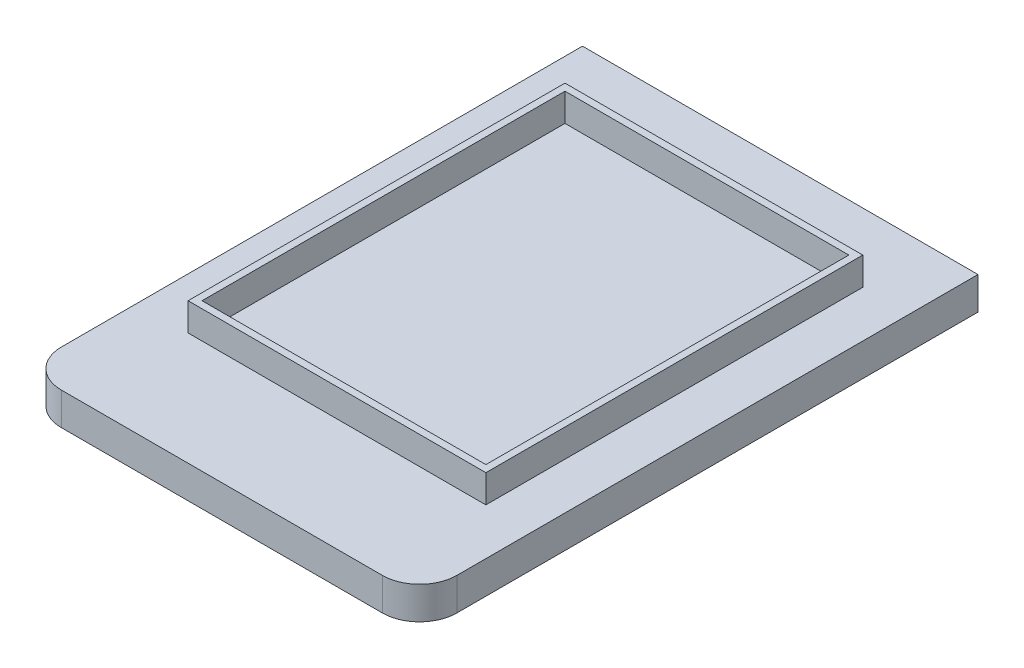
SolidWorks part; units mm, degrees
ref_plane "Front Plane" through (0, 0, 0) normal (0, 0, 1) x (1, 0, 0)
ref_plane "Top Plane" through (0, 0, 0) normal (0, 1, 0) x (1, 0, 0)
ref_plane "Right Plane" through (0, 0, 0) normal (1, 0, 0) x (0, 0, -1)
sketch "Sketch1" plane through (0, 0, 0) normal (0, 1, 0) x (1, 0, 0)
  line L1 (0, 0) -> (85, 0)
  line L2 (0, 0) -> (0, 120)
  line L3 (0, 120) -> (85, 120)
  line L4 (85, 0) -> (85, 120)
  dimension "D1" = 85
  dimension "D2" = 120
extrude "Boss-Extrude1" add sketch "Sketch1" along normal blind 7
fillet "Fillet1" radius 8 2 edges at (85, 3.5, 0) (0, 3.5, 0)
sketch "Sketch2" plane through (0, 7, 0) normal (0, 1, 0) x (1, 0, 0)
  line L0 (11, 105.2396) -> (75, 105.2396)
  line L1 (12.5, 103.7396) -> (73.5, 103.7396)
  line L2 (12.5, 103.7396) -> (12.5, 25.7396)
  line L3 (12.5, 25.7396) -> (73.5, 25.7396)
  line L4 (73.5, 103.7396) -> (73.5, 25.7396)
  line L6 (75, 105.2396) -> (75, 24.2396)
  line L7 (11, 24.2396) -> (75, 24.2396)
  line L8 (11, 105.2396) -> (11, 24.2396)
  line L9 (85, 8) -> (85, 120) construction
  point P10 (75, 29.7141)
  point P11 (75, 24.2396)
  dimension "D1" = 61
  dimension "D2" = 78
  dimension "D3" = 1.5
  dimension "D4" = 10
extrude "Boss-Extrude2" add sketch "Sketch2" along normal blind 6
